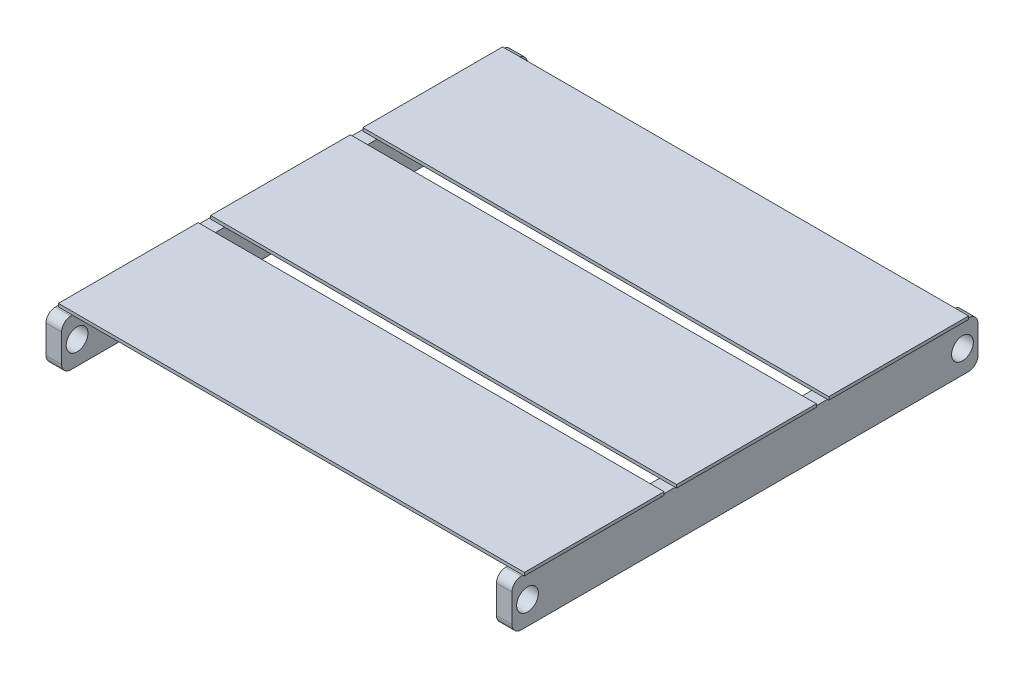
SolidWorks part; units mm, degrees
ref_plane "Front Plane" through (0, 0, 0) normal (0, 0, 1) x (1, 0, 0)
ref_plane "Top Plane" through (0, 0, 0) normal (0, 1, 0) x (1, 0, 0)
ref_plane "Right Plane" through (0, 0, 0) normal (1, 0, 0) x (0, 0, -1)
sketch "Sketch1" plane through (0, 0, 0) normal (1, 0, 0) x (0, 0, -1)
  line L1 (-720, -75) -> (720, -75)
  line L2 (-750, -45) -> (-750, 45)
  line L3 (-720, 75) -> (720, 75)
  line L4 (750, -45) -> (750, 45)
  line L5 (-750, -75) -> (750, 75) construction
  line L6 (-750, 75) -> (750, -75) construction
  arc A0 (-720, -75) -> (-750, -45) centre (-720, -45) cw
  arc A1 (720, -75) -> (750, -45) centre (720, -45) ccw
  arc A2 (720, 75) -> (750, 45) centre (720, 45) cw
  arc A3 (-750, 45) -> (-720, 75) centre (-720, 45) cw
  point P0 (0, 0)
  dimension "D3" = 30
  dimension "D1" = 150
  dimension "D2" = 1500
extrude "Boss-Extrude1" add sketch "Sketch1" along normal blind 50
sketch "Sketch2" plane through (0, 75, 0) normal (0, 1, 0) x (1, 0, 0)
  line L1 (4.674, 265.1042) -> (1504.674, 265.1042)
  line L2 (4.674, 265.1042) -> (4.674, 715.1042)
  line L3 (4.674, 715.1042) -> (1504.674, 715.1042)
  line L4 (1504.674, 265.1042) -> (1504.674, 715.1042)
  line L5 (4.674, 265.1042) -> (1504.674, 715.1042) construction
  line L6 (4.674, 715.1042) -> (1504.674, 265.1042) construction
  point P0 (754.674, 490.1042)
  dimension "D1" = 1500
  dimension "D2" = 450
extrude "Boss-Extrude2" add sketch "Sketch2" along normal blind 10
pattern_linear "LPattern1" count 2 spacing 1450 along (1, 0, 0) of "Boss-Extrude1"
pattern_linear "LPattern2" count 3 spacing 490 along (0, 0, 1) of "Boss-Extrude2"
sketch "Sketch3" plane through (0, 0, 0) normal (-1, 0, 0) x (0, 0, 1)
  line L0 (-750, -45) -> (-750, 45) construction
  line L1 (750, 45) -> (750, -45) construction
  circle A0 centre (-700, 0) radius 35
  circle A1 centre (700, 0) radius 35
  dimension "D1" = 70
  dimension "D2" = 70
  dimension "D3" = 50
  dimension "D4" = 50
extrude "Cut-Extrude1" cut sketch "Sketch3" against normal up to surface (1500 mm away) up to face at (1500, 32.1429, -0.0447)
